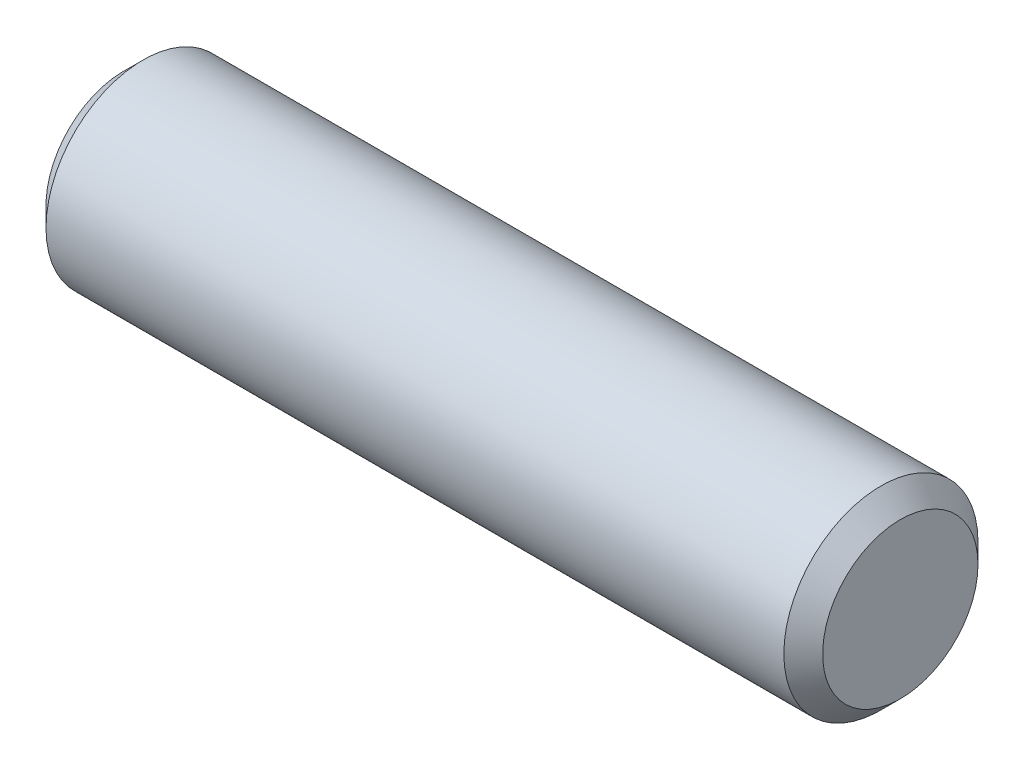
SolidWorks part; units mm, degrees
ref_plane "Front Plane" through (0, 0, 0) normal (0, 0, 1) x (1, 0, 0)
ref_plane "Top Plane" through (0, 0, 0) normal (0, 1, 0) x (1, 0, 0)
ref_plane "Right Plane" through (0, 0, 0) normal (1, 0, 0) x (0, 0, -1)
sketch "Sketch1" plane through (0, 0, 0) normal (0, 0, 1) x (1, 0, 0)
  line L0 (-9.525, 0) -> (9.525, 0) construction
  line L1 (-9.525, 2.3813) -> (-9.525, -2.3813) construction
  line L2 (9.525, 2.3813) -> (9.525, -2.3813) construction
  dimension "Diameter" = 4.7625
  dimension "Length" = 19.05
sketch "Sketch2" plane through (0, 0, 0) normal (1, 0, 0) x (0, 0, -1)
  circle A0 centre (0, 0) radius 2.3813
extrude "Extrude1" add sketch "Sketch2" against normal up to vertex (9.525 mm away) and the other way up to vertex (9.525 mm away) up to point (-9.525, 0, 0) other way up to point (9.525, 0, 0)
chamfer "Chamfer1" distance 0.4763 angle 45 2 edges at (9.525, 0, -2.3813) (-9.525, 0, -2.3813)
equation "\"D1@Chamfer1\" = \"Diameter@Sketch1\"*.1"
